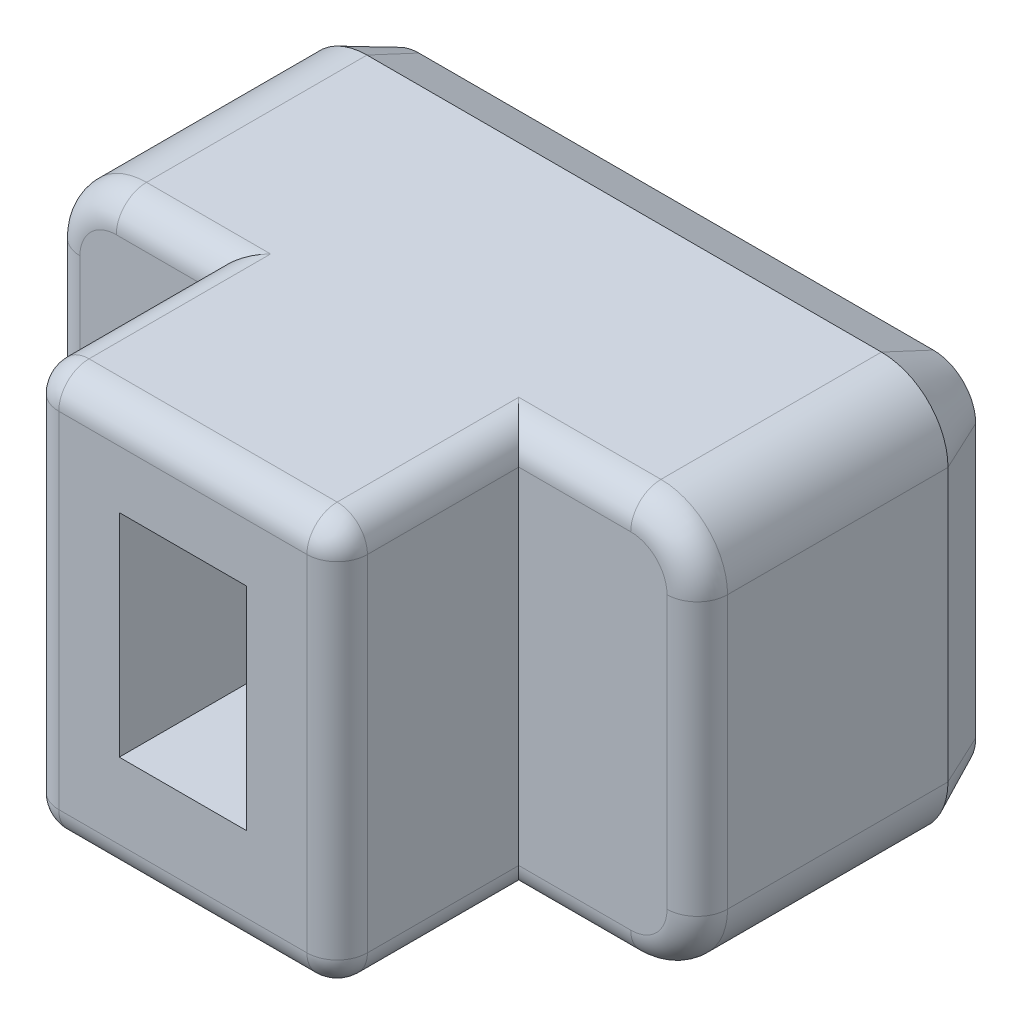
SolidWorks part; units mm, degrees
ref_plane "Plan de face" through (0, 0, 0) normal (0, 0, 1) x (1, 0, 0)
ref_plane "Plan de dessus" through (0, 0, 0) normal (0, 1, 0) x (1, 0, 0)
ref_plane "Plan de droite" through (0, 0, 0) normal (1, 0, 0) x (0, 0, -1)
sketch "Esquisse2" plane through (0, 0, 0) normal (0, 0, 1) x (1, 0, 0)
  line L1 (1.1, 0) -> (9.6, 0)
  line L2 (0, 1.1) -> (0, 5.6)
  line L3 (1.1, 6.7) -> (9.6, 6.7)
  line L4 (10.7, 1.1) -> (10.7, 5.6)
  arc A0 (9.6, 6.7) -> (10.7, 5.6) centre (9.6, 5.6) cw
  arc A1 (9.6, 0) -> (10.7, 1.1) centre (9.6, 1.1) ccw
  arc A2 (1.1, 0) -> (0, 1.1) centre (1.1, 1.1) cw
  arc A3 (0, 5.6) -> (1.1, 6.7) centre (1.1, 5.6) cw
  point P7 (10.7, 6.7)
  point P12 (0, 0)
  point P15 (0, 6.7)
  dimension "D3" = 1.1
  dimension "D1" = 10.7
  dimension "D2" = 6.7
extrude "Boss.-Extru.1" add sketch "Esquisse2" along normal blind 8
sketch "Esquisse3" plane through (0, 0, 8) normal (0, 0, 1) x (1, 0, 0)
  line L0 (0, 5.6) -> (0, 1.1) construction
  line L1 (4.15, 5.25) -> (6.25, 5.25)
  line L2 (4.15, 5.25) -> (4.15, 1.75)
  line L3 (4.15, 1.75) -> (6.25, 1.75)
  line L4 (6.25, 5.25) -> (6.25, 1.75)
  line L5 (10.7, 1.1) -> (10.7, 5.6) construction
  line L6 (9.6, 6.7) -> (1.1, 6.7) construction
  line L7 (1.1, 0) -> (9.6, 0) construction
  dimension "D1" = 2.1
  dimension "D2" = 3.5
  dimension "D3" = 4.15
  dimension "D4" = 4.45
  dimension "D5" = 1.45
  dimension "D6" = 1.75
extrude "Enlèv. mat.-Extru.1" cut sketch "Esquisse3" against normal blind 3
sketch "Esquisse4" plane through (0, 0, 8) normal (0, 0, 1) x (1, 0, 0)
  line L0 (2.65, 6.7) -> (2.65, 0)
  line L1 (9.6, 6.7) -> (1.1, 6.7) construction
  line L2 (1.1, 0) -> (9.6, 0) construction
  line L3 (2.65, 0) -> (7.75, 0)
  line L4 (7.75, 0) -> (7.75, 6.7)
  line L5 (7.75, 6.7) -> (2.65, 6.7)
  line L6 (4.15, 5.25) -> (4.15, 1.75) construction
  line L7 (6.25, 1.75) -> (6.25, 5.25) construction
  dimension "D1" = 1.5
  dimension "D2" = 1.5
extrude "Enlèv. mat.-Extru.2" cut sketch "Esquisse4" against normal blind 3 flip side to cut
fillet "Congé1" radius 0.5 18 edges at (8.675, 0, 5) (10.3778, 0.3222, 5) (10.7, 3.35, 5) (10.3778, 6.3778, 5) (1.875, 6.7, 5) (0.3222, 6.3778, 5) (1.875, 0, 5) (0.3222, 0.3222, 5) (7.75, 6.7, 6.5) (2.65, 6.7, 6.5) (7.75, 0, 6.5) (2.65, 0, 6.5) (2.65, 3.35, 8) (5.2, 6.7, 8) (7.75, 3.35, 8) (5.2, 0, 8) (8.675, 6.7, 5) (0, 3.35, 5)
chamfer "Chanfrein1" distance 0.4 angle 65 8 edges at (5.35, 0, 0) (10.3778, 0.3222, 0) (0.3222, 0.3222, 0) (10.7, 3.35, 0) (0, 3.35, 0) (10.3778, 6.3778, 0) (0.3222, 6.3778, 0) (5.35, 6.7, 0)
ref_plane "Plan1" through (0, 0, 0.2) normal (0, 0, 1) x (1, 0, 0)
sketch "Esquisse5" plane through (0, 0, 0.2) normal (0, 0, 1) x (1, 0, 0)
  line L0 (-0.9378, 5.3566) -> (11.6517, 5.3566) construction
  text T0 "ALT" font "Century Gothic" height 4
